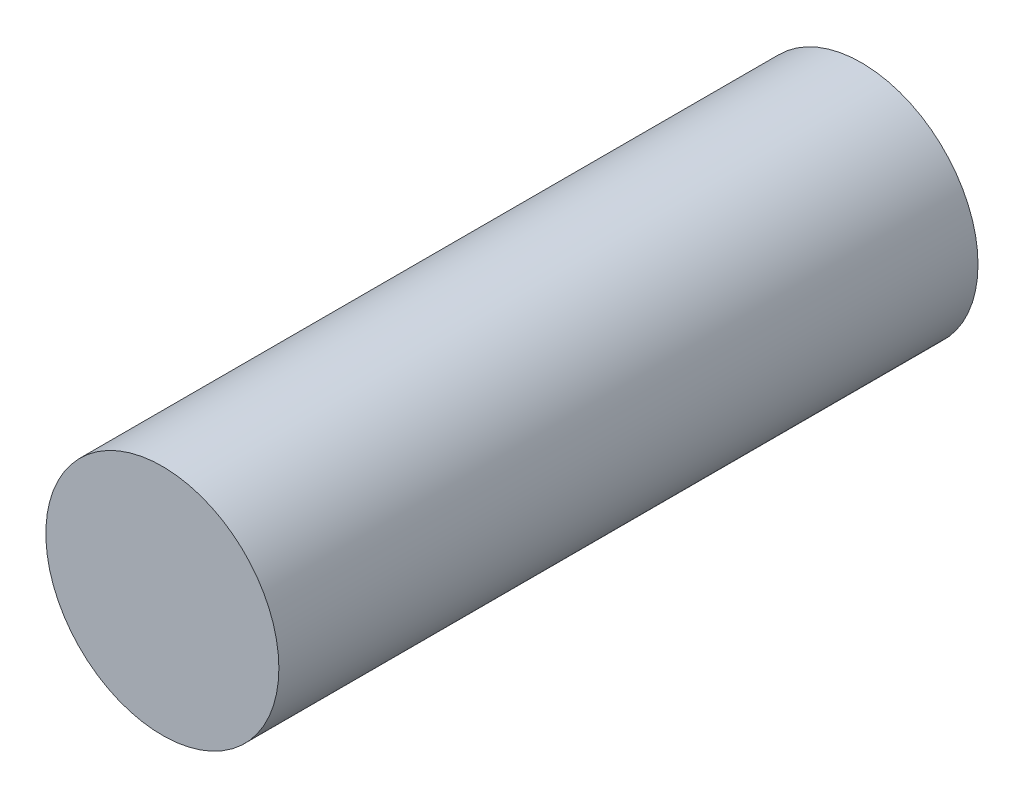
SolidWorks part; units mm, degrees
ref_plane "Plan de face" through (0, 0, 0) normal (0, 0, 1) x (1, 0, 0)
ref_plane "Plan de dessus" through (0, 0, 0) normal (0, 1, 0) x (1, 0, 0)
ref_plane "Plan de droite" through (0, 0, 0) normal (1, 0, 0) x (0, 0, -1)
sketch "Esquisse1" plane through (0, 0, 0) normal (0, 0, 1) x (1, 0, 0)
  circle A0 centre (0, 0) radius 3
  dimension "D1" = 6
extrude "Boss.-Extru.1" add sketch "Esquisse1" along normal blind 18
